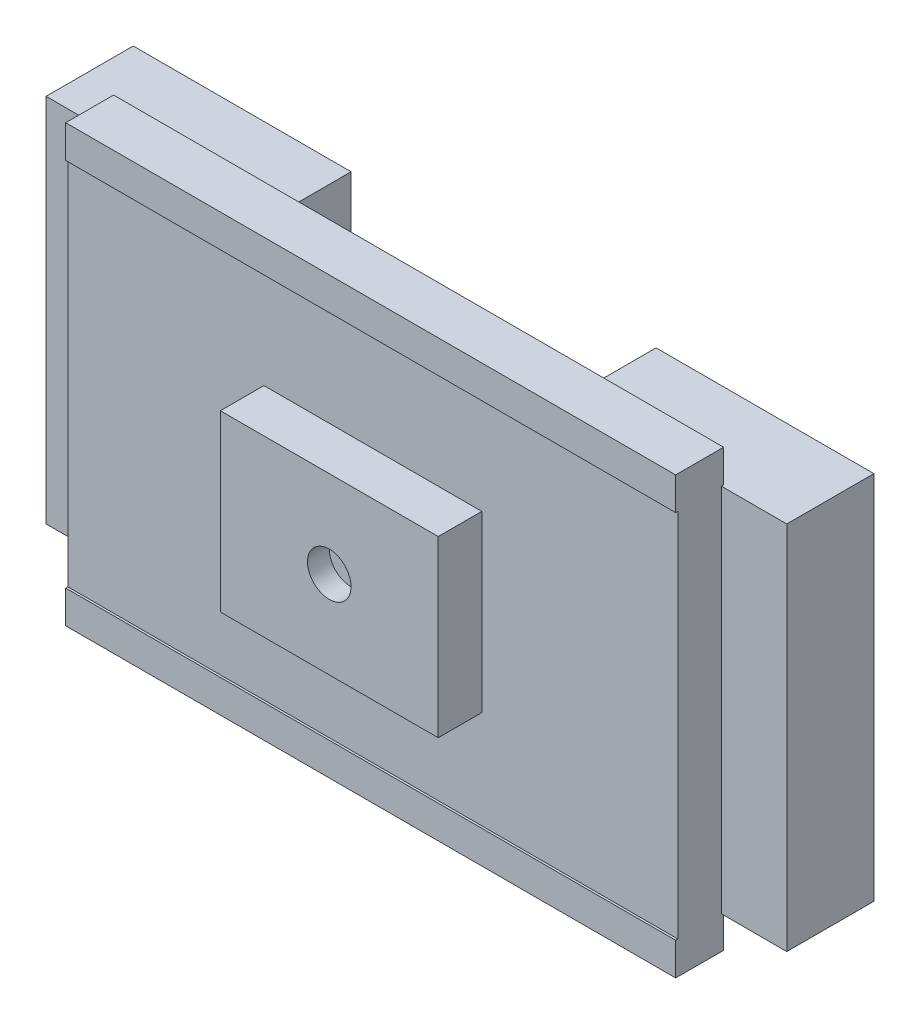
SolidWorks part; units mm, degrees
ref_plane "Front Plane" through (0, 0, 0) normal (0, 0, 1) x (1, 0, 0)
ref_plane "Top Plane" through (0, 0, 0) normal (0, 1, 0) x (1, 0, 0)
ref_plane "Right Plane" through (0, 0, 0) normal (1, 0, 0) x (0, 0, -1)
sketch "Sketch1" plane through (0, 0, 0) normal (0, 0, 1) x (1, 0, 0)
  line L1 (-7, 5) -> (7, 5)
  line L2 (-7, 5) -> (-7, -5)
  line L3 (-7, -5) -> (7, -5)
  line L4 (7, 5) -> (7, -5)
  line L5 (0, -5) -> (0, 5) construction
  line L6 (-7, 0) -> (7, 0) construction
  point P0 (0, 0)
  dimension "D1" = 14
  dimension "D2" = 10
extrude "Boss-Extrude1" add sketch "Sketch1" along normal blind 1
sketch "Sketch2" plane through (0, 0, 1) normal (0, 0, 1) x (1, 0, 0)
  line L7 (-2.5, 2) -> (2.5, 2)
  line L8 (-2.5, 2) -> (-2.5, -2)
  line L9 (-2.5, -2) -> (2.5, -2)
  line L10 (2.5, 2) -> (2.5, -2)
  line L11 (0, -2) -> (0, 2) construction
  line L12 (-2.5, 0) -> (2.5, 0) construction
  point P4 (0, 0)
  point P5 (0, 0)
  dimension "D4" = 5
  dimension "D5" = 4
extrude "Boss-Extrude3" add sketch "Sketch2" along normal blind 1 contours L10 L7 L8 L9
sketch "Sketch3" plane through (0, 0, 0) normal (0, 0, -1) x (-1, 0, 0)
  line L0 (0, -2.4736) -> (0, 2.4736) construction
  line L1 (3.5, 4.25) -> (8.5, 4.25)
  line L2 (3.5, 4.25) -> (3.5, -4.25)
  line L3 (3.5, -4.25) -> (8.5, -4.25)
  line L4 (8.5, 4.25) -> (8.5, -4.25)
  line L5 (6, -4.25) -> (6, 4.25) construction
  line L6 (3.5, 0) -> (8.5, 0) construction
  line L7 (-3.5, 4.25) -> (-3.5, -4.25)
  line L8 (-3.5, 4.25) -> (-8.5, 4.25)
  line L9 (-8.5, 4.25) -> (-8.5, -4.25)
  line L10 (-3.5, -4.25) -> (-8.5, -4.25)
  point P0 (6, 0)
  point P6 (0, 0)
  point P7 (0, 0)
  dimension "D1" = 8.5
  dimension "D2" = 5
  dimension "D3" = 3.5
extrude "Boss-Extrude4" add sketch "Sketch3" along normal blind 2
sketch "Sketch4" plane through (0, 0, 2) normal (0, 0, 1) x (1, 0, 0)
  line L1 (-4, 2.8217) -> (4, 2.8217) construction
  line L2 (-4, 2.8217) -> (-4, -2.8217) construction
  line L3 (-4, -2.8217) -> (4, -2.8217) construction
  line L4 (4, 2.8217) -> (4, -2.8217) construction
  line L5 (0, -2.8217) -> (0, 2.8217) construction
  line L6 (-4, 0) -> (4, 0) construction
  circle A0 centre (0, 0) radius 0.5
  point P0 (0, 0)
  point P4 (0.2425, -0.0642)
  point P5 (-1.4649, 0.0257)
  point P6 (-1.4393, 0.8217)
  point P10 (-1.5, 0)
  dimension "D1" = 1
extrude "Cut-Extrude1" cut sketch "Sketch4" against normal blind 0.5
sketch "Sketch5" plane through (0, 0, 0) normal (0, 0, -1) x (-1, 0, 0)
  line L0 (-7, 5) -> (-7, -5) construction
  line L1 (-7, 5) -> (7, 5)
  line L2 (-7, 5) -> (-7, 4.25)
  line L3 (-7, 4.25) -> (7, 4.25)
  line L4 (7, 5) -> (7, 4.25)
  line L5 (0, 4.25) -> (0, 5) construction
  line L6 (-7, 4.625) -> (7, 4.625) construction
  line L8 (-3.5, 4.25) -> (-7, 4.25) construction
  line L9 (7, 5) -> (-7, 5) construction
  line L10 (7, 5) -> (7, -5) construction
  line L11 (-1.6334, 0) -> (1.6334, 0) construction
  line L12 (-7, -5) -> (-7, -4.25)
  line L13 (-7, -5) -> (7, -5)
  line L14 (7, -5) -> (7, -4.25)
  line L15 (-7, -4.25) -> (7, -4.25)
  point P0 (0, 4.625)
  point P4 (0, 0)
  point P5 (0, 0)
extrude "Boss-Extrude5" add sketch "Sketch5" along normal blind 0.05 and the other way blind 1.05
